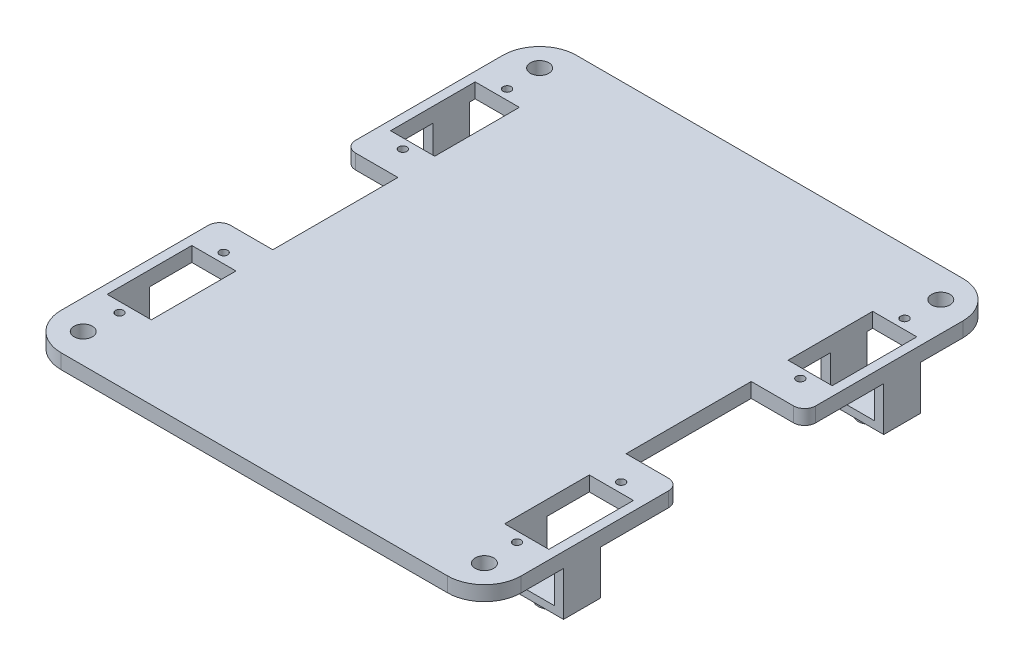
SolidWorks part; units mm, degrees
material "1060 Alloy"
ref_plane "Front Plane" through (0, 0, 0) normal (0, 0, 1) x (1, 0, 0)
ref_plane "Top Plane" through (0, 0, 0) normal (0, 1, 0) x (1, 0, 0)
ref_plane "Right Plane" through (0, 0, 0) normal (1, 0, 0) x (0, 0, -1)
sketch "Sketch1" plane through (0, 0, 0) normal (0, 1, 0) x (1, 0, 0)
  line L1 (-60, -70) -> (60, -70)
  line L2 (-60, -70) -> (-60, 70)
  line L3 (-60, 70) -> (60, 70)
  line L4 (60, -70) -> (60, 70)
  line L5 (-60, -70) -> (60, 70) construction
  line L6 (-60, 70) -> (60, -70) construction
  point P0 (0, 0)
  dimension "D1" = 140
  dimension "D2" = 120
extrude "Boss-Extrude1" add sketch "Sketch1" along normal blind 4
sketch "Sketch2" plane through (0, 4, 0) normal (0, 1, 0) x (1, 0, 0)
  line L0 (60, -70) -> (60, 70) construction
  line L1 (60, 50) -> (48, 50)
  line L2 (60, 50) -> (60, 27)
  line L3 (60, 27) -> (48, 27)
  line L4 (48, 50) -> (48, 27)
  line L5 (-60, 70) -> (-60, -70) construction
  line L6 (-60, 50) -> (-48, 50)
  line L7 (-60, 50) -> (-60, 27)
  line L8 (-60, 27) -> (-48, 27)
  line L9 (-48, 50) -> (-48, 27)
  line L10 (-48, 0) -> (0, 0) construction
  line L19 (60, -27) -> (48, -27)
  line L20 (60, -27) -> (60, -50)
  line L21 (60, -50) -> (48, -50)
  line L22 (48, -27) -> (48, -50)
  line L23 (-60, -27) -> (-48, -27)
  line L24 (-60, -27) -> (-60, -50)
  line L25 (-60, -50) -> (-48, -50)
  line L26 (-48, -27) -> (-48, -50)
  line L27 (0, 0) -> (48, 0) construction
  line L28 (-54, 52.65) -> (-54, 50) construction
  line L29 (-60, -70) -> (60, -70) construction
  line L30 (60, 70) -> (-60, 70) construction
  line L31 (-54, 24.35) -> (-54, 27) construction
  line L32 (-60, 17) -> (-48, 17)
  line L33 (-60, 17) -> (-60, -17)
  line L34 (-60, -17) -> (-48, -17)
  line L35 (-48, 17) -> (-48, -17)
  line L36 (60, 17) -> (48, 17)
  line L37 (60, 17) -> (60, -17)
  line L38 (60, -17) -> (48, -17)
  line L39 (48, 17) -> (48, -17)
  line L40 (-54, -24.35) -> (-54, -27) construction
  line L41 (-54, -50) -> (-54, -52.65) construction
  line L42 (54, 52.65) -> (54, 50) construction
  line L43 (54, 24.35) -> (54, 27) construction
  line L44 (54, -24.35) -> (54, -27) construction
  line L45 (54, -50) -> (54, -52.65) construction
  circle A2 centre (-54, 52.65) radius 1.1
  circle A3 centre (-54, 24.35) radius 1.1
  circle A4 centre (-54, -24.35) radius 1.1
  circle A5 centre (-54, -52.65) radius 1.1
  circle A6 centre (54, 52.65) radius 1.1
  circle A7 centre (54, 24.35) radius 1.1
  circle A8 centre (54, -24.35) radius 1.1
  circle A9 centre (54, -52.65) radius 1.1
  circle A10 centre (-54.5, 62) radius 2.5
  circle A11 centre (54.5, 62) radius 2.5
  circle A12 centre (54.5, -62) radius 2.5
  circle A13 centre (-54.5, -62) radius 2.5
  line M15 (60, -70) -> (60, 70)
  line M17 (-60, 70) -> (-60, -70)
  dimension "D6" = 2.2
  dimension "D15" = 5
  dimension "D1" = 23
  dimension "D2" = 12
  dimension "D3" = 20
  dimension "D4" = 20
  dimension "D5" = 10
  dimension "D7" = 2.65
  dimension "D8" = 2.65
  dimension "D9" = 2.65
  dimension "D10" = 2.65
  dimension "D11" = 2.65
  dimension "D12" = 2.65
  dimension "D13" = 2.65
  dimension "D14" = 2.65
  dimension "D16" = 5.5
  dimension "D17" = 8
  dimension "D18" = 8
  dimension "D19" = 5.5
  dimension "D20" = 5.5
  dimension "D21" = 8
  dimension "D22" = 5.5
  dimension "D23" = 8
extrude "Cut-Extrude1" cut sketch "Sketch2" against normal through all contours L35 L32 L34 M17 | L36 L39 L38 M15 | A2 | A3 | A4 | A5 | A8 | A9 | A6 | A7 | A10 | A11 | A13 | A12
sketch "Sketch3" plane through (0, 4, 0) normal (0, 1, 0) x (1, 0, 0)
  line L1 (60, 70) -> (62.5, 70)
  line L2 (60, 70) -> (60, -70)
  line L3 (60, -70) -> (62.5, -70)
  line L4 (62.5, 70) -> (62.5, -70)
  line L5 (-60, 70) -> (-62.5, 70)
  line L6 (-60, 70) -> (-60, -70)
  line L7 (-60, -70) -> (-62.5, -70)
  line L8 (-62.5, 70) -> (-62.5, -70)
  dimension "D1" = 2.5
extrude "Boss-Extrude2" add sketch "Sketch3" against normal blind 4
sketch "Sketch7" plane through (0, 0, 0) normal (0, -1, 0) x (1, 0, 0)
  line L0 (48, 27) -> (48, 50) construction
  line L1 (48, 48.5) -> (45.5, 48.5)
  line L2 (48, 48.5) -> (48, 38.5)
  line L3 (48, 38.5) -> (45.5, 38.5)
  line L4 (45.5, 48.5) -> (45.5, 38.5)
  line L5 (60, 27) -> (60, 50) construction
  line L6 (60, 48.5) -> (62.5, 48.5)
  line L7 (60, 48.5) -> (60, 38.5)
  line L8 (60, 38.5) -> (62.5, 38.5)
  line L9 (62.5, 48.5) -> (62.5, 38.5)
  line L10 (62.5, 70) -> (62.5, -70) construction
  line L11 (-62.5, -70) -> (-62.5, 70) construction
  line L12 (-62.5, 48.5) -> (-60, 48.5)
  line L13 (-62.5, 48.5) -> (-62.5, 38.5)
  line L14 (-62.5, 38.5) -> (-60, 38.5)
  line L15 (-60, 48.5) -> (-60, 38.5)
  line L16 (-60, 50) -> (-60, 27) construction
  line L17 (-48, 27) -> (-48, 50) construction
  line L18 (-48, 48.5) -> (-45.5, 48.5)
  line L19 (-48, 48.5) -> (-48, 38.5)
  line L20 (-48, 38.5) -> (-45.5, 38.5)
  line L21 (-45.5, 48.5) -> (-45.5, 38.5)
  line L22 (-60, -27) -> (-60, -50) construction
  line L23 (-62.5, -48.5) -> (-60, -48.5)
  line L24 (-62.5, -48.5) -> (-62.5, -38.5)
  line L25 (-62.5, -38.5) -> (-60, -38.5)
  line L26 (-60, -48.5) -> (-60, -38.5)
  line L27 (-48, -50) -> (-48, -27) construction
  line L28 (-48, -38.5) -> (-45.5, -38.5)
  line L29 (-48, -38.5) -> (-48, -48.5)
  line L30 (-48, -48.5) -> (-45.5, -48.5)
  line L31 (-45.5, -38.5) -> (-45.5, -48.5)
  line L32 (48, -50) -> (48, -27) construction
  line L33 (48, -48.5) -> (45.5, -48.5)
  line L34 (48, -48.5) -> (48, -38.5)
  line L35 (48, -38.5) -> (45.5, -38.5)
  line L36 (45.5, -48.5) -> (45.5, -38.5)
  line L37 (60, -50) -> (60, -27) construction
  line L38 (60, -48.5) -> (62.5, -48.5)
  line L39 (60, -48.5) -> (60, -38.5)
  line L40 (60, -38.5) -> (62.5, -38.5)
  line L41 (62.5, -48.5) -> (62.5, -38.5)
  line L45 (60, 50) -> (48, 50) construction
  line L47 (-60, -50) -> (-48, -50) construction
  line L48 (60, -50) -> (48, -50) construction
  dimension "D1" = 10
  dimension "D2" = 1.5
  dimension "D3" = 1.5
  dimension "D4" = 1.5
  dimension "D5" = 1.5
  dimension "D6" = 1.5
extrude "Boss-Extrude6" add sketch "Sketch7" along normal blind 10
sketch "Sketch8" plane through (0, -10, 0) normal (0, -1, 0) x (1, 0, 0)
  line L1 (-62.5, 48.5) -> (-45.5, 48.5)
  line L2 (-62.5, 48.5) -> (-62.5, 38.5)
  line L3 (-62.5, 38.5) -> (-45.5, 38.5)
  line L4 (-45.5, 48.5) -> (-45.5, 38.5)
  line L5 (-62.5, -38.5) -> (-45.5, -38.5)
  line L6 (-62.5, -38.5) -> (-62.5, -48.5)
  line L7 (-62.5, -48.5) -> (-45.5, -48.5)
  line L8 (-45.5, -38.5) -> (-45.5, -48.5)
  line L9 (45.5, -38.5) -> (62.5, -38.5)
  line L10 (45.5, -38.5) -> (45.5, -48.5)
  line L11 (45.5, -48.5) -> (62.5, -48.5)
  line L12 (62.5, -38.5) -> (62.5, -48.5)
  line L13 (45.5, 48.5) -> (62.5, 48.5)
  line L14 (45.5, 48.5) -> (45.5, 38.5)
  line L15 (45.5, 38.5) -> (62.5, 38.5)
  line L16 (62.5, 48.5) -> (62.5, 38.5)
extrude "Boss-Extrude7" add sketch "Sketch8" along normal blind 2
sketch "Sketch9" plane through (0, -12, 0) normal (0, -1, 0) x (1, 0, 0)
  line L0 (-54, 43.5) -> (-54, 48.5) construction
  line L1 (-45.5, 48.5) -> (-62.5, 48.5) construction
  line L2 (-54, 43.5) -> (-45.5, 43.5) construction
  line L3 (-45.5, 38.5) -> (-45.5, 48.5) construction
  line L4 (-54, -38.5) -> (-54, -43.5) construction
  line L5 (-45.5, -38.5) -> (-62.5, -38.5) construction
  line L6 (-54, -43.5) -> (-45.5, -43.5) construction
  line L7 (-45.5, -48.5) -> (-45.5, -38.5) construction
  line L8 (54, -38.5) -> (54, -43.5) construction
  line L9 (62.5, -38.5) -> (45.5, -38.5) construction
  line L10 (54, -43.5) -> (62.5, -43.5) construction
  line L11 (62.5, -48.5) -> (62.5, -38.5) construction
  line L12 (54, 48.5) -> (54, 43.5) construction
  line L13 (62.5, 48.5) -> (45.5, 48.5) construction
  line L14 (54, 43.5) -> (62.5, 43.5) construction
  line L15 (62.5, 38.5) -> (62.5, 48.5) construction
  circle A0 centre (54, 43.5) radius 3.4
  circle A1 centre (-54, 43.5) radius 3.4
  circle A2 centre (-54, -43.5) radius 3.4
  circle A3 centre (54, -43.5) radius 3.4
  dimension "D1" = 6.8
  dimension "D2" = 6.8
  dimension "D3" = 6.8
  dimension "D4" = 6.8
extrude "Boss-Extrude8" add sketch "Sketch9" along normal blind 2
sketch "Sketch10" plane through (0, 4, 0) normal (0, 1, 0) x (1, 0, 0)
  line L0 (62.5, -70) -> (62.5, 70) construction
  line L1 (60, 17) -> (62.5, 17)
  line L2 (60, 17) -> (60, -17)
  line L3 (60, -17) -> (62.5, -17)
  line L4 (62.5, 17) -> (62.5, -17)
  line L5 (-62.5, 70) -> (-62.5, -70) construction
  line L6 (-60, 17) -> (-62.5, 17)
  line L7 (-60, 17) -> (-60, -17)
  line L8 (-60, -17) -> (-62.5, -17)
  line L9 (-62.5, 17) -> (-62.5, -17)
extrude "Cut-Extrude2" cut sketch "Sketch10" against normal through all
fillet "Fillet1" radius 10 1 edges at (62.5, 2, -70)
fillet "Fillet2" radius 10 1 edges at (-62.5, 2, -70)
fillet "Fillet3" radius 10 1 edges at (-62.5, 2, 70)
fillet "Fillet4" radius 10 1 edges at (62.5, 2, 70)
fillet "Fillet5" radius 3 1 edges at (62.5, 2, -17)
fillet "Fillet6" radius 3 1 edges at (-62.5, 2, 17)
fillet "Fillet7" radius 3 1 edges at (62.5, 2, 17)
fillet "Fillet8" radius 3 1 edges at (-62.5, 2, -17)
